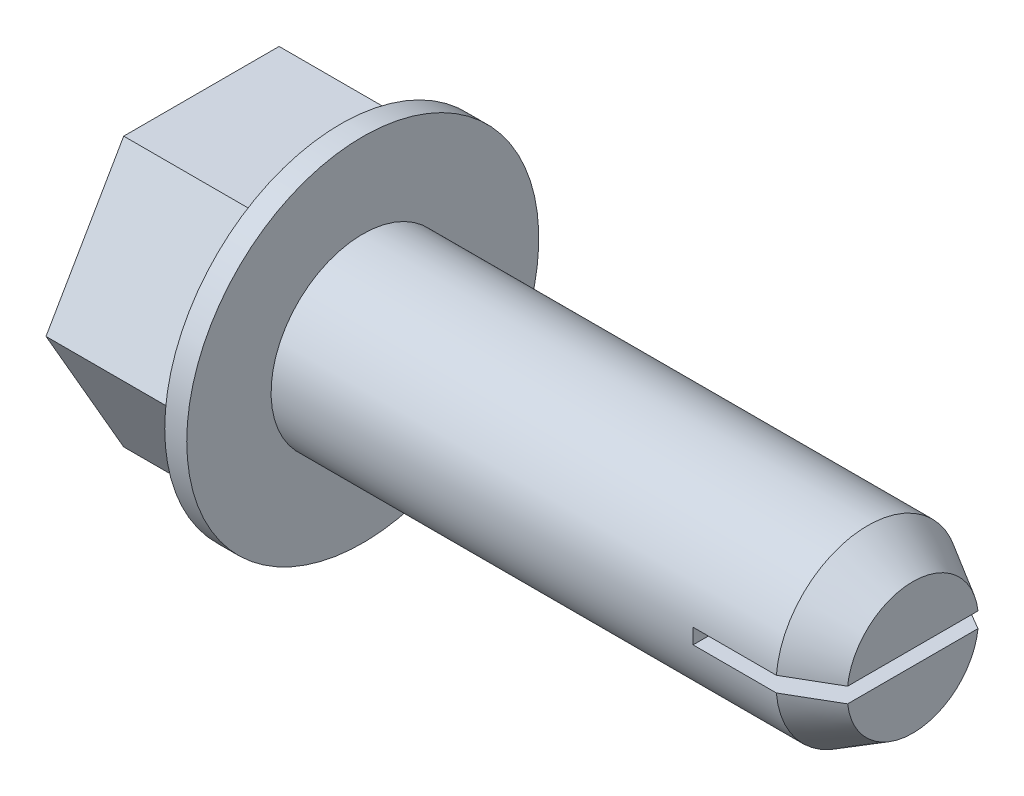
SolidWorks part; units mm, degrees
ref_plane "Front Plane" through (0, 0, 0) normal (0, 0, 1) x (1, 0, 0)
ref_plane "Top Plane" through (0, 0, 0) normal (0, 1, 0) x (1, 0, 0)
ref_plane "Right Plane" through (0, 0, 0) normal (1, 0, 0) x (0, 0, -1)
ref_plane "Plane1" through (-0.762, 0, 0) normal (-1, 0, 0) x (0, -1, 0)
sketch "Sketch1" plane through (-0.762, 0, 0) normal (-1, 0, 0) x (0, -1, 0)
  circle A0 centre (0, 0) radius 6.096
extrude "Boss-Extrude1" add sketch "Sketch1" against normal blind 0.762
sketch "Sketch2" plane through (0, 0, 0) normal (1, 0, 0) x (0, 0, -1)
  circle A0 centre (0, 0) radius 3.175
extrude "Boss-Extrude2" add sketch "Sketch2" along normal blind 19.05
sketch "Sketch3" plane through (19.05, 0, 0) normal (1, 0, 0) x (0, 0, -1)
  line L0 (-3.164, -0.2646) -> (3.164, -0.2646)
  arc A0 (3.164, -0.2646) -> (-3.164, -0.2646) centre (0, 0) ccw
extrude "Cut-Extrude1" cut sketch "Sketch3" against normal blind 4.445
sketch "Sketch4" plane through (14.605, 0, 0) normal (1, 0, 0) x (0, 0, -1)
  line L0 (3.164, 0.2646) -> (-3.164, 0.2646)
  arc A0 (-3.164, 0.2646) -> (3.164, 0.2646) centre (0, 0) cw
extrude "Boss-Extrude3" add sketch "Sketch4" along normal blind 4.445
sketch "Sketch5" plane through (-0.762, 0, 0) normal (-1, 0, 0) x (0, 0, 1)
  line L0 (-2.691, -4.6609) -> (-5.3819, 0)
  line L1 (-5.3819, 0) -> (-2.691, 4.6609)
  line L2 (-2.691, 4.6609) -> (2.691, 4.6609)
  line L3 (2.691, 4.6609) -> (5.3819, 0)
  line L4 (5.3819, 0) -> (2.691, -4.6609)
  line L5 (2.691, -4.6609) -> (-2.691, -4.6609)
extrude "Boss-Extrude4" add sketch "Sketch5" along normal blind 4.826
hole_wizard "Hole1" positions "Sketch7" profile "Sketch6" legacy
sketch "Sketch7" plane through (-5.588, 0, 0) normal (-1, 0, 0) x (0, 0, 1)
  point P0 (0, 0)
sketch "Sketch6" plane through (-5.588, 0, 0) normal (0, 1, 0) x (0, 0, 1)
  line L0 (0, 0) -> (0, 0.9652)
  line L1 (0, 0.9652) -> (3.7287, 0.9652)
  line L2 (3.7287, 0.9652) -> (3.7287, 0)
  line L3 (3.7287, 0) -> (0, 0)
  line L4 (0, 110) -> (0, -10) construction
  dimension "Diameter" = 7.4574
  dimension "Depth" = 0.9652
chamfer "Chamfer1" distance 0.9017 angle 60 2 edges at (19.05, 3.175, 0) (19.05, -3.175, 0)
